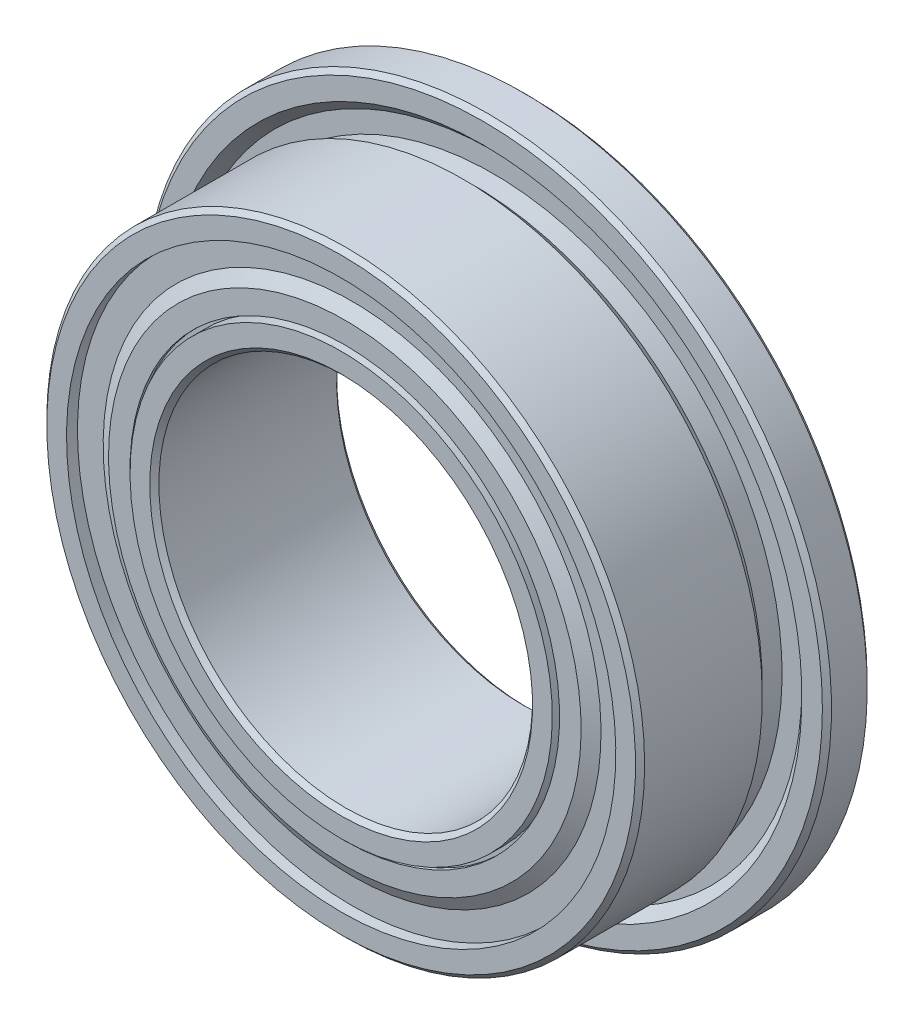
SolidWorks part; units mm, degrees
ref_plane "Front Plane" through (0, 0, 0) normal (0, 0, 1) x (1, 0, 0)
ref_plane "Top Plane" through (0, 0, 0) normal (0, 1, 0) x (1, 0, 0)
ref_plane "Right Plane" through (0, 0, 0) normal (1, 0, 0) x (0, 0, -1)
sketch "Sketch1" plane through (0, 0, 0) normal (1, 0, 0) x (0, 0, -1)
  line L0 (0, 4) -> (0, -4) construction
  line L1 (-1.25, 4) -> (1.25, 4) construction
  line L2 (0, 0) -> (1.25, 0) construction
  line L3 (1.25, 4.6) -> (1.25, -4.6) construction
  line L4 (1.25, -4.6) -> (0.65, -4.6) construction
  line L5 (1.25, 2.5) -> (0, 2.5) construction
  line L6 (1.25, 2.5) -> (1.25, -2.5) construction
  dimension "OD" = 8
  dimension "Width" = 2.5
  dimension "Flange Thickness" = 0.6
  dimension "ID" = 5
  dimension "Flange OD" = 9.2
sketch "Sketch2" plane through (0, 0, 0) normal (1, 0, 0) x (0, 0, -1)
  line L0 (1.25, 4.6) -> (0.65, 4.6)
  line L1 (0.65, 4.6) -> (0.65, 4.2652)
  line L2 (0.3848, 4) -> (-1.25, 4)
  line L3 (-1.25, 4) -> (-1.25, 3.5125)
  line L4 (-1.25, 3.5125) -> (-0.3018, 3.5125)
  line L5 (1.25, 4.6) -> (1.25, -4.6) construction
  line L6 (1.25, 3.5125) -> (1.25, 4.6)
  line L7 (1.25, 2.5) -> (-1.25, 2.5)
  line L8 (-1.25, 2.5) -> (-1.25, 2.9875)
  line L9 (-1.25, 2.9875) -> (-0.3018, 2.9875)
  line L10 (1.25, 2.9875) -> (1.25, 2.5)
  line L11 (0, 4) -> (0, 2.5) construction
  line L12 (-0.4, 3.25) -> (0.4, 3.25) construction
  line L13 (0.3018, 3.5125) -> (1.25, 3.5125)
  line L14 (0.3018, 2.9875) -> (1.25, 2.9875)
  line L15 (0.65, 4.2652) -> (0.7826, 4.1326)
  line L16 (0.7826, 4.1326) -> (0.7826, 3.8674)
  line L17 (0.7826, 3.8674) -> (0.5174, 3.8674)
  line L18 (0.5174, 3.8674) -> (0.3848, 4)
  line L19 (0.65, 4) -> (0.7826, 3.8674) construction
  line L20 (0.7826, 4.1326) -> (0.5174, 3.8674) construction
  line L21 (0.3848, 4) -> (0.65, 4) construction
  line L22 (0.65, 4) -> (0.65, 4.2652) construction
  line L23 (-1.25, 0) -> (1.25, 0) construction
  circle A0 centre (0, 3.25) radius 0.4 construction
  arc A1 (-0.3018, 3.5125) -> (0.3018, 3.5125) centre (0, 3.25) cw
  arc A2 (-0.3018, 2.9875) -> (0.3018, 2.9875) centre (0, 3.25) ccw
  dimension "Ball Dia." = 0.8
  dimension "D2" = 135
  dimension "D3" = 0.375
  dimension "Race Thikness" = 0.4875
  dimension "D4" = 0.525
revolve "Revolve1" add sketch "Sketch2" angle 360 about L2
fillet "Fillet1" radius 0.0609 3 edges at (0, -4.6, -1.25) (0, -4.6, -0.65) (0, -4, 1.25) profile chamfer
sketch "Sketch3" plane through (0, 0, 0) normal (0, 0, 1) x (1, 0, 0)
  line L0 (-2.5, 0) -> (2.5, 0) construction
  line L1 (-4, 0) -> (4, 0) construction
  point P5 (0, 0)
  dimension "ID2" = 5
  dimension "OD2" = 8
fillet "Fillet2" radius 0.0609 2 edges at (0, -2.5, -1.25) (0, -2.5, 1.25) profile chamfer
sketch "Sketch7" plane through (0, 0, 0) normal (0, 0, 1) x (1, 0, 0)
  line L0 (0, 3.65) -> (0, 2.85)
  line L1 (0, 4.6) -> (0, -4.6) construction
  line L2 (-0.4527, 3.65) -> (0, 0) construction
  line L3 (0, 0) -> (0.4527, 3.65) construction
  line L4 (0.4527, 3.65) -> (-0.4527, 3.65) construction
  circle A0 centre (0, 3.25) radius 0.4 construction
  circle A1 centre (0, 0) radius 3.65 construction
  circle A2 centre (0, 0) radius 2.85 construction
  arc A4 (0, 3.65) -> (0, 2.85) centre (0, 3.25) ccw
  dimension "D1" = 14.139
revolve "Revolve3" add sketch "Sketch7" angle 360 about L0
pattern_circular "CirPattern3" count 21 over 360 about axis through (0, 0, 0) along (0, 0, 1) of bodies 107
sketch "Sketch8" plane through (0, 0, 0) normal (1, 0, 0) x (0, 0, -1)
  line L1 (-1.25, 3.5125) -> (-1.055, 3.5125)
  line L2 (-1.25, 3.5125) -> (-1.25, 3.675)
  line L3 (-1.25, 3.675) -> (-1.055, 3.675)
  line L4 (-1.055, 3.5125) -> (-1.055, 3.675)
  line L5 (1.25, 3.5125) -> (1.055, 3.5125)
  line L6 (1.25, 3.5125) -> (1.25, 3.675)
  line L7 (1.25, 3.675) -> (1.055, 3.675)
  line L8 (1.055, 3.5125) -> (1.055, 3.675)
  line L9 (1.25, 2.9875) -> (1.055, 2.9875)
  line L10 (1.25, 2.9875) -> (1.25, 2.825)
  line L11 (1.25, 2.825) -> (1.055, 2.825)
  line L12 (1.055, 2.9875) -> (1.055, 2.825)
  line L13 (-1.25, 2.9875) -> (-1.055, 2.9875)
  line L14 (-1.25, 2.9875) -> (-1.25, 2.825)
  line L15 (-1.25, 2.825) -> (-1.055, 2.825)
  line L16 (-1.055, 2.9875) -> (-1.055, 2.825)
  dimension "D1" = 0.1625
  dimension "D2" = 0.195
revolve "Cut-Revolve1" cut sketch "Sketch8" angle 360 about L2
sketch "Sketch9" plane through (0, 0, 0) normal (1, 0, 0) x (0, 0, -1)
  line L0 (-1.055, 3.675) -> (-1.055, 3.3179)
  line L1 (-1.055, 3.3179) -> (-1.1525, 3.149)
  line L2 (-1.1525, 3.149) -> (-1.1525, 2.8737)
  line L3 (1.1525, 2.8737) -> (1.1525, 2.825) construction
  line L4 (1.055, 3.675) -> (1.055, 3.3179)
  line L5 (1.055, 3.3179) -> (1.1525, 3.149)
  line L6 (1.1525, 3.149) -> (1.1525, 2.8737)
  line L7 (1.25, 2.825) -> (1.055, 2.825) construction
  line L8 (-1.1037, 3.675) -> (-1.1037, 3.3309)
  line L9 (-1.1037, 3.3309) -> (-1.2013, 3.162)
  line L10 (-1.2013, 3.162) -> (-1.2013, 2.8737)
  line L11 (-1.055, 3.675) -> (-1.1037, 3.675)
  line L12 (-1.1525, 2.8737) -> (-1.2013, 2.8737)
  line L13 (1.1038, 3.675) -> (1.1038, 3.3309)
  line L14 (1.1038, 3.3309) -> (1.2013, 3.162)
  line L15 (1.2013, 3.162) -> (1.2013, 2.8737)
  line L16 (1.055, 3.675) -> (1.1038, 3.675)
  line L17 (1.1525, 2.8737) -> (1.2013, 2.8737)
  line L18 (-1.055, 3.3179) -> (-1.055, 2.5308) construction
  line L19 (1.055, 3.3179) -> (1.055, 3.675) construction
  line L20 (-1.055, 2.825) -> (-1.25, 2.825) construction
  line L22 (-1.1525, 2.8737) -> (-1.1525, 2.825) construction
  dimension "D2" = 150
  dimension "D1" = 150
  dimension "D5" = 0.195
  dimension "D3" = 0.0488
  dimension "D4" = 0.0488
  dimension "D6" = 0.3571
revolve "Revolve4" add sketch "Sketch9" angle 360 about L2
equation "\"D1@Fillet1\"=\"Race Thikness@Sketch2\"/8"
equation "\"ID2@Sketch3\" = \"ID@Sketch1\""
equation "\"OD2@Sketch3\" = \"OD@Sketch1\""
equation "\"D1@Fillet2\"=\"Race Thikness@Sketch2\"/8"
equation "\"D1@CirPattern3\"=360/\"D1@Sketch7\"-4"
equation "\"D1@Sketch8\"=\"Race Thikness@Sketch2\"/3"
equation "\"D2@Sketch8\"=\"Race Thikness@Sketch2\"/2.5"
equation "\"D3@Sketch9\"=\"D5@Sketch9\"/4"
equation "\"D4@Sketch9\"=\"D5@Sketch9\"/4"
equation "\"D1@Sketch9\"=\"D2@Sketch9\""
equation "\"Ball Dia.@Sketch2\" = \"D1@Sketch2\"*.5"
equation "\"D4@Sketch2\"=((\"OD@Sketch1\"-\"ID@Sketch1\")/2)*.35"
